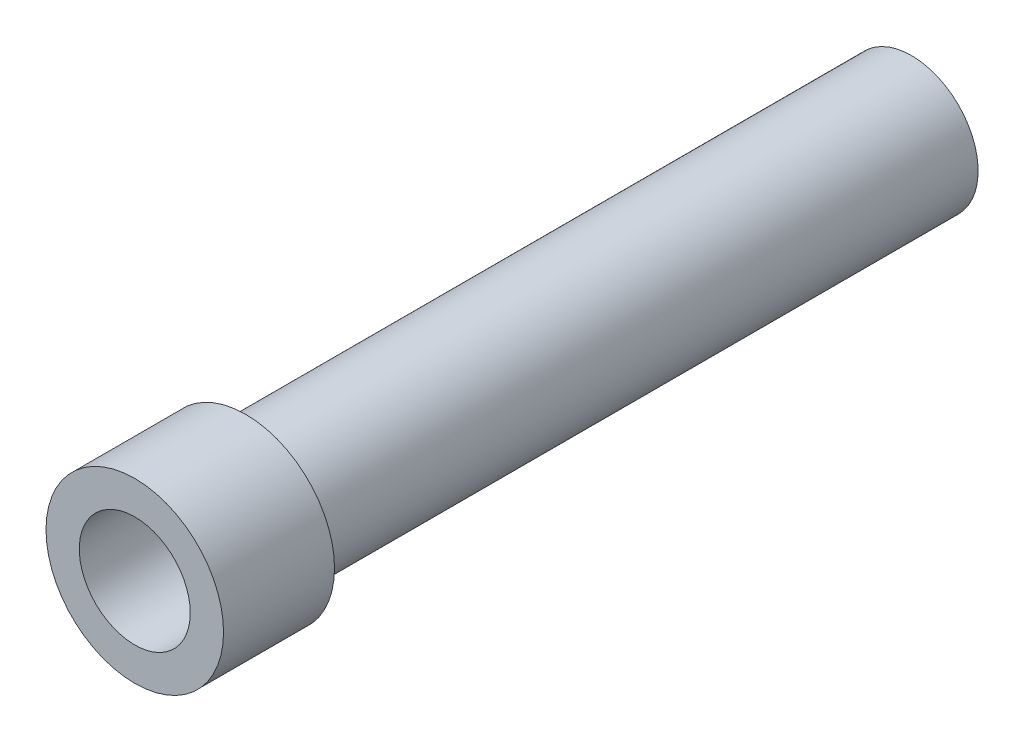
SolidWorks part; units mm, degrees
material "3.3547 (EN-AW 5083)"
ref_plane "Ebene vorne" through (0, 0, 0) normal (0, 0, 1) x (1, 0, 0)
ref_plane "Ebene oben" through (0, 0, 0) normal (0, 1, 0) x (1, 0, 0)
ref_plane "Ebene rechts" through (0, 0, 0) normal (1, 0, 0) x (0, 0, -1)
sketch "Skizze1" plane through (0, 0, 0) normal (0, 0, 1) x (1, 0, 0)
  circle A0 centre (-21.2024, 3.9585) radius 4
extrude "Aufsatz-Linear austragen1" add sketch "Skizze1" along normal blind 35
sketch "Skizze2" plane through (0, 0, 35) normal (0, 0, 1) x (1, 0, 0)
  circle A0 centre (-21.2024, 3.9585) radius 2.5
extrude "Schnitt-Linear austragen1" cut sketch "Skizze2" against normal blind 27
sketch "Skizze3" plane through (0, 0, 0) normal (0, 0, -1) x (-1, 0, 0)
  circle A0 centre (21.2024, 3.9585) radius 12.7694
  circle A1 centre (21.2024, 3.9585) radius 3
extrude "Schnitt-Linear austragen2" cut sketch "Skizze3" against normal blind 30
